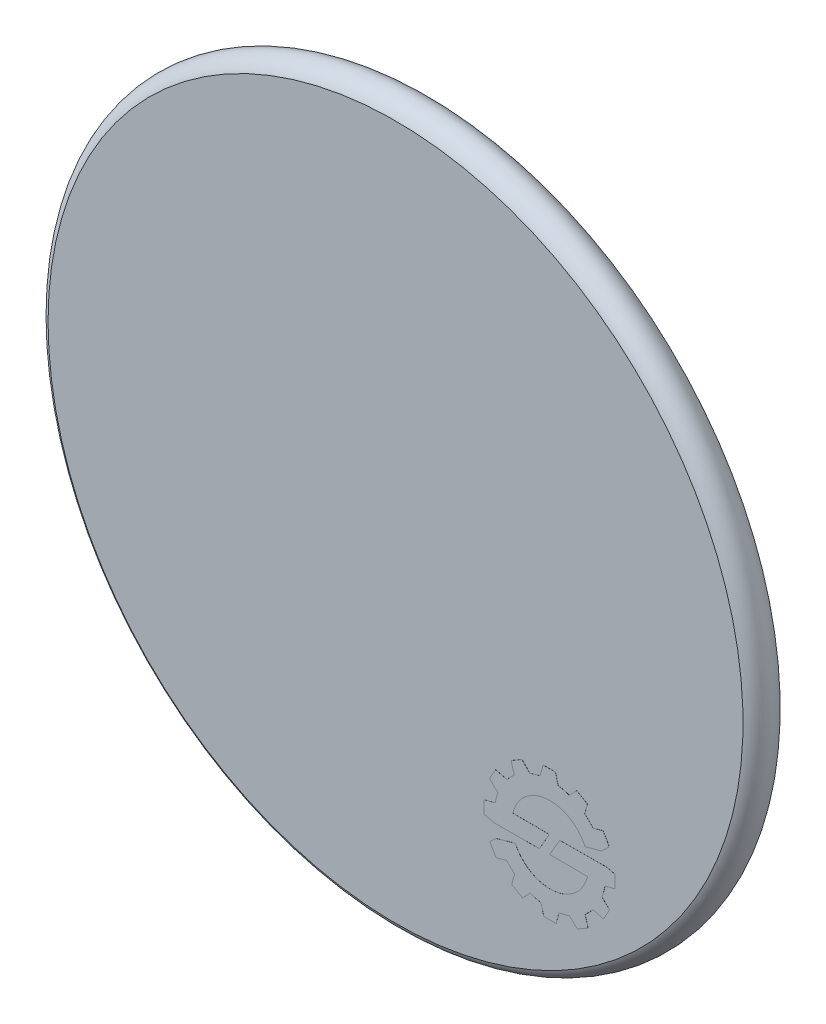
SolidWorks part; units mm, degrees
ref_plane "Front Plane" through (0, 0, 0) normal (0, 0, 1) x (1, 0, 0)
ref_plane "Top Plane" through (0, 0, 0) normal (0, 1, 0) x (1, 0, 0)
ref_plane "Right Plane" through (0, 0, 0) normal (1, 0, 0) x (0, 0, -1)
sketch "Sketch1" plane through (0, 0, 0) normal (0, 1, 0) x (1, 0, 0)
  line L0 (0, 0) -> (-40, 0)
  line L3 (-40, 0) -> (-42, 1.5)
  line L4 (0, 0) -> (0, -3)
  line L5 (0, -3) -> (-42, -3)
  line L6 (-42, -3) -> (-44.5, -3)
  line L8 (-44.5, 1.5) -> (-42, 1.5)
  arc A0 (-44.5, 1.5) -> (-44.5, -3) centre (-43.5625, -0.75) ccw
  dimension "D1" = 40
  dimension "D2" = 42
revolve "Revolve1" add sketch "Sketch1" angle 360 about L4
sketch "Sketch5" plane through (0, 0, 3) normal (0, 0, 1) x (1, 0, 0)
  line L0 (16.6947, -18.7297) -> (16.1934, -18.2222)
  line L1 (16.1934, -18.2222) -> (16.1083, -18.2709)
  line L2 (14.8898, -18.991) -> (14.8169, -19.0457)
  line L3 (14.8169, -19.0457) -> (14.8685, -19.2432)
  line L4 (15.1116, -20.0667) -> (15.221, -20.4222)
  line L5 (15.221, -20.4222) -> (14.8777, -20.7655)
  line L6 (12.1187, -22.2757) -> (12.0518, -22.4124)
  line L7 (12.0518, -22.4124) -> (12.3374, -22.6859)
  line L8 (12.1004, -26.8973) -> (12.617, -27.0189)
  line L9 (12.617, -27.0189) -> (15.4915, -27.0189)
  line L10 (24.1878, -23.6491) -> (24.2911, -23.8497)
  line L11 (24.2911, -23.8497) -> (24.4856, -23.798)
  line L12 (25.543, -23.5093) -> (26.3999, -23.2723)
  line L13 (26.3999, -23.2723) -> (26.886, -22.8014)
  line L14 (26.6186, -21.0056) -> (26.5609, -20.9326)
  line L15 (26.5609, -20.9326) -> (26.2145, -21.0329)
  line L16 (24.4734, -20.4404) -> (24.2364, -20.2277)
  line L17 (24.2364, -20.2277) -> (24.3914, -19.6808)
  line L18 (23.4221, -18.3013) -> (23.1942, -18.1706)
  line L19 (23.1942, -18.1706) -> (22.7202, -18.6659)
  line L20 (22.7202, -18.6659) -> (22.2462, -19.1612)
  line L21 (22.2462, -19.1612) -> (22.0669, -19.0943)
  line L22 (20.5294, -17.5963) -> (20.496, -17.4778)
  line L23 (20.496, -17.4778) -> (19.6938, -17.4778)
  line L24 (20.3805, -25.8885) -> (19.7515, -26.9885)
  line L25 (19.7515, -26.9885) -> (22.1641, -26.9885)
  line L26 (12.4438, -29.0486) -> (12.0822, -29.4102)
  line L27 (12.0822, -29.4102) -> (12.2189, -29.6351)
  line L28 (14.747, -30.8961) -> (15.2544, -31.4035)
  line L29 (15.2544, -31.4035) -> (15.1299, -31.8623)
  line L30 (16.1721, -33.4697) -> (16.2906, -33.5274)
  line L31 (16.2906, -33.5274) -> (16.4608, -33.3482)
  line L32 (16.9408, -32.8438) -> (17.2538, -32.5156)
  line L33 (17.2538, -32.5156) -> (17.5273, -32.6098)
  line L34 (20.3562, -34.2202) -> (20.5871, -34.2202)
  line L35 (20.5871, -34.2202) -> (20.7451, -33.567)
  line L36 (25.2057, -30.4403) -> (25.3029, -30.3218)
  line L37 (25.3029, -30.3218) -> (25.6007, -30.4069)
  line L38 (26.2692, -30.5892) -> (26.6399, -30.6894)
  line L39 (26.6399, -30.6894) -> (26.7888, -30.4281)
  line L40 (26.6916, -28.5928) -> (26.4485, -28.3649)
  line L41 (26.4485, -28.3649) -> (26.5731, -27.9882)
  line L42 (27.5089, -26.7606) -> (28.1166, -26.6087)
  line L43 (28.1166, -26.6087) -> (28.1166, -25.8034)
  line L44 (28.1166, -25.8034) -> (28.1166, -24.9982)
  line L45 (28.1166, -24.9982) -> (27.6153, -24.8706)
  line L46 (27.6153, -24.8706) -> (27.1139, -24.746)
  line L47 (27.1139, -24.746) -> (24.1209, -24.746)
  spline S0 degree 3 poles (18.8916, -17.4839) (18.8916, -17.49) (18.8126, -17.7999) (18.7184, -18.1767) knots 0 0 0 0 1 1 1 1
  spline S1 degree 3 poles (18.7184, -18.1767) (18.5239, -18.9424) (18.5756, -18.8603) (18.2262, -18.9393) knots 0 0 0 0 1 1 1 1
  spline S2 degree 3 poles (18.2262, -18.9393) (18.135, -18.9576) (17.8737, -19.0335) (17.6488, -19.1065) knots 0 0 0 0 1 1 1 1
  spline S3 degree 3 poles (17.6488, -19.1065) (17.424, -19.1794) (17.2295, -19.2402) (17.2174, -19.2402) knots 0 0 0 0 1 1 1 1
  spline S4 degree 3 poles (17.2174, -19.2402) (17.2052, -19.2402) (16.9682, -19.0123) (16.6947, -18.7297) knots 0 0 0 0 1 1 1 1
  spline S5 degree 3 poles (16.1083, -18.2709) (15.3881, -18.6871) (14.9476, -18.9485) (14.8898, -18.991) knots 0 0 0 0 1 1 1 1
  spline S6 degree 3 poles (14.8685, -19.2432) (14.9232, -19.4529) (14.9415, -19.5197) (15.1116, -20.0667) knots 0 0 0 0 1 1 1 1
  spline S7 degree 3 poles (14.8777, -20.7655) (14.6893, -20.9539) (14.4796, -21.1727) (14.4128, -21.2517) knots 0 0 0 0 1 1 1 1
  spline S8 degree 3 poles (14.4128, -21.2517) (14.3459, -21.3307) (14.27, -21.3975) (14.2456, -21.3975) knots 0 0 0 0 1 1 1 1
  spline S9 degree 3 poles (14.2456, -21.3975) (14.2213, -21.3975) (14.0573, -21.355) (13.881, -21.3064) knots 0 0 0 0 1 1 1 1
  spline S10 degree 3 poles (13.881, -21.3064) (13.2399, -21.121) (12.8418, -21.0268) (12.8175, -21.0511) knots 0 0 0 0 1 1 1 1
  spline S11 degree 3 poles (12.8175, -21.0511) (12.8054, -21.0663) (12.7324, -21.1879) (12.6595, -21.3216) knots 0 0 0 0 1 1 1 1
  spline S12 degree 3 poles (12.6595, -21.3216) (12.5836, -21.4553) (12.4468, -21.6953) (12.3557, -21.8533) knots 0 0 0 0 1 1 1 1
  spline S13 degree 3 poles (12.3557, -21.8533) (12.2645, -22.0113) (12.1582, -22.2028) (12.1187, -22.2757) knots 0 0 0 0 1 1 1 1
  spline S14 degree 3 poles (12.3374, -22.6859) (12.4924, -22.8378) (12.7324, -23.0687) (12.8722, -23.2024) knots 0 0 0 0 1 1 1 1
  spline S15 degree 3 poles (12.8722, -23.2024) (13.009, -23.3331) (13.1214, -23.4486) (13.1214, -23.4546) knots 0 0 0 0 1 1 1 1
  spline S16 degree 3 poles (13.1214, -23.4546) (13.1214, -23.4638) (13.0819, -23.5792) (13.0333, -23.716) knots 0 0 0 0 1 1 1 1
  spline S17 degree 3 poles (13.0333, -23.716) (12.9877, -23.8527) (12.9178, -24.1019) (12.8783, -24.269) knots 0 0 0 0 1 1 1 1
  spline S18 degree 3 poles (12.8783, -24.269) (12.8418, -24.4361) (12.8023, -24.6123) (12.7902, -24.6609) knots 0 0 0 0 1 1 1 1
  spline S19 degree 3 poles (12.7902, -24.6609) (12.7689, -24.7491) (12.7568, -24.7551) (12.3162, -24.8645) knots 0 0 0 0 1 1 1 1
  spline S20 degree 3 poles (12.3162, -24.8645) (12.064, -24.9253) (11.7571, -25.0013) (11.6325, -25.0316) knots 0 0 0 0 1 1 1 1
  spline S21 degree 3 poles (11.6325, -25.0316) (11.5079, -25.059) (11.3864, -25.0955) (11.3651, -25.1137) knots 0 0 0 0 1 1 1 1
  spline S22 degree 3 poles (11.3651, -25.1137) (11.3377, -25.135) (11.3286, -25.3234) (11.3317, -25.8916) knots 0 0 0 0 1 1 1 1
  spline S23 degree 3 poles (11.3317, -25.8916) (11.3317, -26.3018) (11.3469, -26.6603) (11.359, -26.6877) knots 0 0 0 0 1 1 1 1
  spline S24 degree 3 poles (11.359, -26.6877) (11.3742, -26.715) (11.4319, -26.7454) (11.4866, -26.7545) knots 0 0 0 0 1 1 1 1
  spline S25 degree 3 poles (11.4866, -26.7545) (11.5413, -26.7636) (11.8178, -26.8274) (12.1004, -26.8973) knots 0 0 0 0 1 1 1 1
  spline S26 degree 3 poles (15.4915, -27.0189) (17.7461, -27.0189) (18.3781, -27.0097) (18.4145, -26.9794) knots 0 0 0 0 1 1 1 1
  spline S27 degree 3 poles (18.4145, -26.9794) (18.4389, -26.9611) (18.5969, -26.7029) (18.764, -26.4112) knots 0 0 0 0 1 1 1 1
  spline S28 degree 3 poles (18.764, -26.4112) (18.9311, -26.1195) (19.2076, -25.6394) (19.3778, -25.3446) knots 0 0 0 0 1 1 1 1
  spline S29 degree 3 poles (19.3778, -25.3446) (19.5449, -25.0499) (19.6847, -24.7977) (19.6847, -24.7886) knots 0 0 0 0 1 1 1 1
  spline S30 degree 3 poles (19.6847, -24.7886) (19.6847, -24.7794) (18.6394, -24.7703) (17.3602, -24.7703) knots 0 0 0 0 1 1 1 1
  spline S31 degree 3 poles (17.3602, -24.7703) (15.139, -24.7703) (15.0357, -24.7673) (15.0357, -24.7156) knots 0 0 0 0 1 1 1 1
  spline S32 degree 3 poles (15.0357, -24.7156) (15.0357, -24.6458) (15.218, -24.1079) (15.3152, -23.8892) knots 0 0 0 0 1 1 1 1
  spline S33 degree 3 poles (15.3152, -23.8892) (16.1295, -22.0691) (18.0074, -20.8992) (19.9733, -20.9843) knots 0 0 0 0 1 1 1 1
  spline S34 degree 3 poles (19.9733, -20.9843) (21.4926, -21.0481) (22.7809, -21.7105) (23.7077, -22.8955) knots 0 0 0 0 1 1 1 1
  spline S35 degree 3 poles (23.7077, -22.8955) (23.8171, -23.0384) (23.9082, -23.1599) (23.9082, -23.169) knots 0 0 0 0 1 1 1 1
  spline S36 degree 3 poles (23.9082, -23.169) (23.9082, -23.1781) (23.9478, -23.245) (23.9964, -23.3179) knots 0 0 0 0 1 1 1 1
  spline S37 degree 3 poles (23.9964, -23.3179) (24.0419, -23.3908) (24.1301, -23.5397) (24.1878, -23.6491) knots 0 0 0 0 1 1 1 1
  spline S38 degree 3 poles (24.4856, -23.798) (24.595, -23.7706) (25.069, -23.64) (25.543, -23.5093) knots 0 0 0 0 1 1 1 1
  spline S39 degree 3 poles (26.886, -22.8014) (27.1534, -22.54) (27.3722, -22.3182) (27.3722, -22.3061) knots 0 0 0 0 1 1 1 1
  spline S40 degree 3 poles (27.3722, -22.3061) (27.3722, -22.2909) (27.2324, -22.0447) (27.0653, -21.7561) knots 0 0 0 0 1 1 1 1
  spline S41 degree 3 poles (27.0653, -21.7561) (26.8951, -21.4674) (26.7371, -21.197) (26.7159, -21.1545) knots 0 0 0 0 1 1 1 1
  spline S42 degree 3 poles (26.7159, -21.1545) (26.6916, -21.1119) (26.649, -21.0451) (26.6186, -21.0056) knots 0 0 0 0 1 1 1 1
  spline S43 degree 3 poles (26.2145, -21.0329) (26.0231, -21.0846) (25.7648, -21.1636) (25.6372, -21.2031) knots 0 0 0 0 1 1 1 1
  spline S44 degree 3 poles (25.6372, -21.2031) (25.5096, -21.2426) (25.385, -21.276) (25.3576, -21.276) knots 0 0 0 0 1 1 1 1
  spline S45 degree 3 poles (25.3576, -21.276) (25.3333, -21.276) (25.2513, -21.2122) (25.1784, -21.1332) knots 0 0 0 0 1 1 1 1
  spline S46 degree 3 poles (25.1784, -21.1332) (24.9596, -20.8962) (24.7256, -20.6652) (24.4734, -20.4404) knots 0 0 0 0 1 1 1 1
  spline S47 degree 3 poles (24.3914, -19.6808) (24.6071, -18.912) (24.6041, -18.9637) (24.4643, -18.8907) knots 0 0 0 0 1 1 1 1
  spline S48 degree 3 poles (24.4643, -18.8907) (24.4005, -18.8573) (24.1908, -18.7388) (23.9994, -18.6294) knots 0 0 0 0 1 1 1 1
  spline S49 degree 3 poles (23.9994, -18.6294) (23.808, -18.52) (23.5467, -18.3711) (23.4221, -18.3013) knots 0 0 0 0 1 1 1 1
  spline S50 degree 3 poles (22.0669, -19.0943) (21.8299, -19.0092) (21.3467, -18.8847) (21.1584, -18.8603) knots 0 0 0 0 1 1 1 1
  spline S51 degree 3 poles (21.1584, -18.8603) (20.815, -18.8148) (20.8363, -18.8421) (20.6935, -18.3043) knots 0 0 0 0 1 1 1 1
  spline S52 degree 3 poles (20.6935, -18.3043) (20.6236, -18.0399) (20.5658, -17.7999) (20.5658, -17.7695) knots 0 0 0 0 1 1 1 1
  spline S53 degree 3 poles (20.5658, -17.7695) (20.5658, -17.7391) (20.5506, -17.6601) (20.5294, -17.5963) knots 0 0 0 0 1 1 1 1
  spline S54 degree 3 poles (19.6938, -17.4778) (19.2562, -17.4778) (18.8946, -17.4808) (18.8916, -17.4839) knots 0 0 0 0 1 1 1 1
  spline S55 degree 3 poles (21.0702, -24.7673) (21.0368, -24.7794) (20.7542, -25.2413) (20.3805, -25.8885) knots 0 0 0 0 1 1 1 1
  spline S56 degree 3 poles (22.1641, -26.9885) (24.1453, -26.9885) (24.5767, -26.9946) (24.5767, -27.028) knots 0 0 0 0 1 1 1 1
  spline S57 degree 3 poles (24.5767, -27.028) (24.5767, -27.0523) (24.5433, -27.1829) (24.5008, -27.3197) knots 0 0 0 0 1 1 1 1
  spline S58 degree 3 poles (24.5008, -27.3197) (24.285, -28.0398) (23.8171, -28.8116) (23.2762, -29.3494) knots 0 0 0 0 1 1 1 1
  spline S59 degree 3 poles (23.2762, -29.3494) (22.5774, -30.0361) (21.8238, -30.4433) (20.8089, -30.6834) knots 0 0 0 0 1 1 1 1
  spline S60 degree 3 poles (20.8089, -30.6834) (20.3228, -30.7958) (19.5631, -30.814) (19.0466, -30.7259) knots 0 0 0 0 1 1 1 1
  spline S61 degree 3 poles (19.0466, -30.7259) (17.6124, -30.4767) (16.5306, -29.787) (15.7011, -28.5837) knots 0 0 0 0 1 1 1 1
  spline S62 degree 3 poles (15.7011, -28.5837) (15.6434, -28.4986) (15.5401, -28.3254) (15.4763, -28.1978) knots 0 0 0 0 1 1 1 1
  spline S63 degree 3 poles (15.4763, -28.1978) (15.4094, -28.0672) (15.3395, -27.9608) (15.3243, -27.9608) knots 0 0 0 0 1 1 1 1
  spline S64 degree 3 poles (15.3243, -27.9608) (15.3061, -27.9608) (15.1754, -27.9942) (15.0357, -28.0337) knots 0 0 0 0 1 1 1 1
  spline S65 degree 3 poles (15.0357, -28.0337) (14.8929, -28.0763) (14.3672, -28.2191) (13.8658, -28.3558) knots 0 0 0 0 1 1 1 1
  spline S66 degree 3 poles (13.8658, -28.3558) (13.3645, -28.4956) (12.9208, -28.6232) (12.8783, -28.6445) knots 0 0 0 0 1 1 1 1
  spline S67 degree 3 poles (12.8783, -28.6445) (12.8358, -28.6688) (12.6413, -28.8481) (12.4438, -29.0486) knots 0 0 0 0 1 1 1 1
  spline S68 degree 3 poles (12.2189, -29.6351) (12.3496, -29.8538) (12.5289, -30.1577) (12.6352, -30.3461) knots 0 0 0 0 1 1 1 1
  spline S69 degree 3 poles (12.6352, -30.3461) (12.6626, -30.3947) (12.7324, -30.5102) (12.7871, -30.6013) knots 0 0 0 0 1 1 1 1
  spline S70 degree 3 poles (12.7871, -30.6013) (12.8844, -30.7593) (12.8904, -30.7624) (13.0029, -30.7441) knots 0 0 0 0 1 1 1 1
  spline S71 degree 3 poles (13.0029, -30.7441) (13.0667, -30.735) (13.2247, -30.6925) (13.3553, -30.653) knots 0 0 0 0 1 1 1 1
  spline S72 degree 3 poles (13.3553, -30.653) (13.486, -30.6104) (13.7261, -30.5375) (13.8901, -30.4859) knots 0 0 0 0 1 1 1 1
  spline S73 degree 3 poles (13.8901, -30.4859) (14.0542, -30.4342) (14.2001, -30.3917) (14.2153, -30.3917) knots 0 0 0 0 1 1 1 1
  spline S74 degree 3 poles (14.2153, -30.3917) (14.2305, -30.3917) (14.4705, -30.6196) (14.747, -30.8961) knots 0 0 0 0 1 1 1 1
  spline S75 degree 3 poles (15.1299, -31.8623) (15.06, -32.1145) (14.9749, -32.4062) (14.9445, -32.5126) knots 0 0 0 0 1 1 1 1
  spline S76 degree 3 poles (14.9445, -32.5126) (14.8898, -32.6949) (14.8898, -32.7921) (14.9476, -32.7921) knots 0 0 0 0 1 1 1 1
  spline S77 degree 3 poles (14.9476, -32.7921) (14.9627, -32.7921) (15.0387, -32.8316) (15.1177, -32.8772) knots 0 0 0 0 1 1 1 1
  spline S78 degree 3 poles (15.1177, -32.8772) (15.3729, -33.0322) (16.0505, -33.4089) (16.1721, -33.4697) knots 0 0 0 0 1 1 1 1
  spline S79 degree 3 poles (16.4608, -33.3482) (16.5549, -33.2509) (16.7707, -33.023) (16.9408, -32.8438) knots 0 0 0 0 1 1 1 1
  spline S80 degree 3 poles (17.5273, -32.6098) (17.7795, -32.6949) (18.2687, -32.8195) (18.5361, -32.865) knots 0 0 0 0 1 1 1 1
  spline S81 degree 3 poles (18.5361, -32.865) (18.6303, -32.8833) (18.6485, -32.8985) (18.6667, -32.9835) knots 0 0 0 0 1 1 1 1
  spline S82 degree 3 poles (18.6667, -32.9835) (18.7123, -33.2145) (18.9676, -34.1777) (18.9919, -34.2081) knots 0 0 0 0 1 1 1 1
  spline S83 degree 3 poles (18.9919, -34.2081) (19.0101, -34.2324) (19.1833, -34.2415) (19.5722, -34.2324) knots 0 0 0 0 1 1 1 1
  spline S84 degree 3 poles (19.5722, -34.2324) (19.8761, -34.2263) (20.2286, -34.2233) (20.3562, -34.2202) knots 0 0 0 0 1 1 1 1
  spline S85 degree 3 poles (20.7451, -33.567) (20.8332, -33.2084) (20.9244, -32.9015) (20.9457, -32.8833) knots 0 0 0 0 1 1 1 1
  spline S86 degree 3 poles (20.9457, -32.8833) (20.9639, -32.8681) (21.055, -32.8377) (21.1462, -32.8225) knots 0 0 0 0 1 1 1 1
  spline S87 degree 3 poles (21.1462, -32.8225) (21.3802, -32.78) (22.0942, -32.5764) (22.1307, -32.546) knots 0 0 0 0 1 1 1 1
  spline S88 degree 3 poles (22.1307, -32.546) (22.1459, -32.5308) (22.1945, -32.5186) (22.2431, -32.5186) knots 0 0 0 0 1 1 1 1
  spline S89 degree 3 poles (22.2431, -32.5186) (22.31, -32.5186) (22.4133, -32.6068) (22.787, -32.9896) knots 0 0 0 0 1 1 1 1
  spline S90 degree 3 poles (22.787, -32.9896) (23.0423, -33.2479) (23.2732, -33.4606) (23.2975, -33.4606) knots 0 0 0 0 1 1 1 1
  spline S91 degree 3 poles (23.2975, -33.4606) (23.3248, -33.4606) (23.3735, -33.4424) (23.4069, -33.4181) knots 0 0 0 0 1 1 1 1
  spline S92 degree 3 poles (23.4069, -33.4181) (23.4403, -33.3968) (23.5163, -33.3512) (23.574, -33.3178) knots 0 0 0 0 1 1 1 1
  spline S93 degree 3 poles (23.574, -33.3178) (23.6895, -33.2509) (23.9721, -33.0869) (24.1361, -32.9896) knots 0 0 0 0 1 1 1 1
  spline S94 degree 3 poles (24.1361, -32.9896) (24.1939, -32.9562) (24.3306, -32.8772) (24.44, -32.8134) knots 0 0 0 0 1 1 1 1
  spline S95 degree 3 poles (24.44, -32.8134) (24.6648, -32.6827) (24.6679, -32.6706) (24.5767, -32.3698) knots 0 0 0 0 1 1 1 1
  spline S96 degree 3 poles (24.5767, -32.3698) (24.3944, -31.762) (24.3033, -31.44) (24.3033, -31.3913) knots 0 0 0 0 1 1 1 1
  spline S97 degree 3 poles (24.3033, -31.3913) (24.3033, -31.364) (24.3549, -31.2941) (24.4187, -31.2364) knots 0 0 0 0 1 1 1 1
  spline S98 degree 3 poles (24.4187, -31.2364) (24.598, -31.0753) (25.0994, -30.5709) (25.2057, -30.4403) knots 0 0 0 0 1 1 1 1
  spline S99 degree 3 poles (25.6007, -30.4069) (25.7648, -30.4524) (26.0656, -30.5345) (26.2692, -30.5892) knots 0 0 0 0 1 1 1 1
  spline S100 degree 3 poles (26.7888, -30.4281) (27.2871, -29.5439) (27.4026, -29.3312) (27.4026, -29.3039) knots 0 0 0 0 1 1 1 1
  spline S101 degree 3 poles (27.4026, -29.3039) (27.4026, -29.2765) (27.2659, -29.1367) (26.6916, -28.5928) knots 0 0 0 0 1 1 1 1
  spline S102 degree 3 poles (26.5731, -27.9882) (26.6429, -27.7815) (26.7311, -27.4595) (26.7675, -27.2771) knots 0 0 0 0 1 1 1 1
  spline S103 degree 3 poles (26.7675, -27.2771) (26.807, -27.0918) (26.8526, -26.9368) (26.8708, -26.9277) knots 0 0 0 0 1 1 1 1
  spline S104 degree 3 poles (26.8708, -26.9277) (26.886, -26.9216) (27.1747, -26.8457) (27.5089, -26.7606) knots 0 0 0 0 1 1 1 1
  spline S105 degree 3 poles (24.1209, -24.746) (22.4741, -24.746) (21.1006, -24.7551) (21.0702, -24.7673) knots 0 0 0 0 1 1 1 1
extrude "Boss-Extrude2" add sketch "Sketch5" along normal blind 0.01
sketch "Sketch8" plane through (0, 0, 0) normal (0, 0, -1) x (-1, 0, 0)
  line L0 (-1.1168, 18.2598) -> (-0.383, 18.161)
  line L1 (-0.383, 18.161) -> (-0.383, 17.3426)
  line L2 (-7.0999, 8.0574) -> (-7.495, 6.8721)
  line L3 (-7.495, 6.8721) -> (-8.638, 6.9709)
  line L4 (-23.2572, -11.43) -> (-21.4086, -9.4968)
  line L5 (-10.9946, -5.6303) -> (-10.7124, -6.477)
  line L6 (-10.7124, -6.477) -> (-11.0087, -6.6746)
  line L7 (-16.3427, -7.4789) -> (-20.1386, -7.4648)
  line L8 (-20.1386, -7.4648) -> (-20.4914, -7.8176)
  line L9 (-20.4914, -12.2061) -> (-20.1527, -12.5589)
  line L10 (-20.1527, -12.5589) -> (0.1532, -12.5589)
  line L11 (0.1532, -12.5589) -> (20.4591, -12.5589)
  line L12 (20.4591, -12.5589) -> (20.8401, -12.2626)
  line L13 (11.3715, -6.6746) -> (11.0752, -6.477)
  line L14 (11.0752, -6.477) -> (11.3574, -5.6303)
  line L15 (21.7714, -9.5109) -> (23.62, -11.43)
  line L16 (8.9868, 6.9709) -> (7.8296, 6.8721)
  line L17 (7.8296, 6.8721) -> (7.6039, 7.6764)
  line L18 (1.4373, 16.3266) -> (0.7459, 16.5806)
  line L19 (0.7459, 16.5806) -> (0.7459, 17.3849)
  line L20 (0.7459, 17.3849) -> (0.7459, 18.1751)
  line L21 (0.7459, 18.1751) -> (1.6349, 18.2598)
  line L22 (3.4975, 18.7678) -> (3.4975, 19.1206)
  line L23 (3.4975, 19.1206) -> (0.1391, 19.1629)
  line L24 (-3.9531, 6.5899) -> (-4.9268, 6.6746)
  line L25 (-4.9268, 6.6746) -> (-4.828, 7.3237)
  line L26 (-6.2815, -1.5381) -> (-5.7735, -3.0762)
  line L27 (-5.7735, -3.0762) -> (-6.4367, -3.1609)
  line L28 (-9.7105, -3.4713) -> (-10.3737, -3.556)
  line L29 (-10.3737, -3.556) -> (-10.7406, -2.4553)
  line L30 (11.1175, -2.3989) -> (10.7365, -3.5419)
  line L31 (10.7365, -3.5419) -> (9.9463, -3.4572)
  line L32 (-14.9598, -3.9088) -> (-15.6371, -3.9934)
  line L33 (-15.6371, -3.9934) -> (-15.5948, -3.2456)
  line L34 (-15.5948, -3.2456) -> (-15.5525, -2.4977)
  line L35 (-15.5525, -2.4977) -> (-14.0003, -2.032)
  line L36 (15.9577, -3.2456) -> (16, -3.9934)
  line L37 (16, -3.9934) -> (15.3227, -3.9088)
  line L38 (14.3208, -2.0461) -> (15.9153, -2.4977)
  line L39 (15.9153, -2.4977) -> (15.9577, -3.2456)
  line L40 (-4.8986, -5.9267) -> (-4.4329, -7.493)
  line L41 (-4.4329, -7.493) -> (-4.7293, -7.874)
  line L42 (-5.8158, -9.7649) -> (-5.9146, -10.16)
  line L43 (-5.9146, -10.16) -> (-4.7716, -10.16)
  line L44 (5.1344, -10.16) -> (6.2774, -10.16)
  line L45 (6.2774, -10.16) -> (6.1786, -9.7649)
  line L46 (5.0921, -7.874) -> (4.7958, -7.493)
  line L47 (4.7958, -7.493) -> (5.2614, -5.9267)
  line L48 (11.1175, -9.652) -> (10.2709, -10.7103)
  line L49 (10.2709, -10.7103) -> (0.1814, -10.7103)
  line L50 (0.1814, -10.7103) -> (-9.908, -10.7103)
  line L51 (-9.908, -10.7103) -> (-10.7124, -9.6943)
  line L52 (-5.9428, -4.3886) -> (-5.3643, -4.3744)
  line L53 (-5.3643, -4.3744) -> (-4.8986, -5.9267)
  line L54 (-14.0003, -9.9483) -> (-14.0003, -10.795)
  line L55 (-14.0003, -10.795) -> (-16.6814, -10.795)
  line L56 (-16.6814, -10.795) -> (-19.3625, -10.795)
  line L57 (-19.3625, -10.795) -> (-19.4048, -10.1036)
  line L58 (-16.6531, -9.0593) -> (-14.0003, -9.1017)
  line L59 (-14.0003, -9.1017) -> (-14.0003, -9.9483)
  line L60 (19.7253, -9.9483) -> (19.7253, -10.795)
  line L61 (19.7253, -10.795) -> (17.0442, -10.795)
  line L62 (17.0442, -10.795) -> (14.3631, -10.795)
  line L63 (14.3631, -10.795) -> (14.3208, -10.1036)
  line L64 (17.0724, -9.0593) -> (19.7253, -9.1017)
  line L65 (19.7253, -9.1017) -> (19.7253, -9.9483)
  line L66 (-12.5327, 8.89) -> (-7.4668, 8.89)
  line L67 (-7.4668, 8.89) -> (-7.0858, 9.8496)
  line L68 (-6.0134, 12.1073) -> (-5.3219, 13.4056)
  line L69 (-5.3219, 13.4056) -> (-10.6841, 13.4056)
  line L70 (-10.6841, 13.4056) -> (-16.0464, 13.4056)
  line L71 (-16.0464, 13.4056) -> (-16.0464, 12.5166)
  line L72 (7.5333, 9.7085) -> (7.8579, 8.89)
  line L73 (7.8579, 8.89) -> (12.9096, 8.89)
  line L74 (16.4092, 12.5307) -> (16.4092, 13.4056)
  line L75 (16.4092, 13.4056) -> (11.047, 13.4056)
  line L76 (11.047, 13.4056) -> (5.6989, 13.4056)
  line L77 (5.6989, 13.4056) -> (6.4468, 11.9662)
  spline S0 degree 3 poles (-3.2899, 18.9795) (-3.4592, 18.542) (-3.2335, 18.3445) (-2.542, 18.3445) knots 0 0 0 0 1 1 1 1
  spline S1 degree 3 poles (-2.542, 18.3445) (-2.1751, 18.3445) (-1.526, 18.3021) (-1.1168, 18.2598) knots 0 0 0 0 1 1 1 1
  spline S2 degree 3 poles (-0.383, 17.3426) (-0.383, 16.7358) (-0.4395, 16.51) (-0.5665, 16.51) knots 0 0 0 0 1 1 1 1
  spline S3 degree 3 poles (-0.5665, 16.51) (-0.6794, 16.51) (-1.145, 16.3125) (-1.6248, 16.0867) knots 0 0 0 0 1 1 1 1
  spline S4 degree 3 poles (-1.6248, 16.0867) (-2.6267, 15.5787) (-3.7838, 14.478) (-4.6164, 13.2503) knots 0 0 0 0 1 1 1 1
  spline S5 degree 3 poles (-4.6164, 13.2503) (-5.3643, 12.1497) (-6.5919, 9.5956) (-7.0999, 8.0574) knots 0 0 0 0 1 1 1 1
  spline S6 degree 3 poles (-8.638, 6.9709) (-12.2505, 7.2531) (-12.702, 7.2531) (-13.1395, 6.9144) knots 0 0 0 0 1 1 1 1
  spline S7 degree 3 poles (-13.1395, 6.9144) (-13.7745, 6.3923) (-14.353, 5.5033) (-14.353, 5.0236) knots 0 0 0 0 1 1 1 1
  spline S8 degree 3 poles (-14.353, 5.0236) (-14.353, 4.7837) (-13.9861, 3.4996) (-13.5487, 2.159) knots 0 0 0 0 1 1 1 1
  spline S9 degree 3 poles (-13.5487, 2.159) (-13.0971, 0.8184) (-12.7726, -0.3104) (-12.8149, -0.3528) knots 0 0 0 0 1 1 1 1
  spline S10 degree 3 poles (-12.8149, -0.3528) (-12.9137, -0.4516) (-15.1997, -1.1148) (-15.4396, -1.1289) knots 0 0 0 0 1 1 1 1
  spline S11 degree 3 poles (-15.4396, -1.1289) (-15.5807, -1.1289) (-15.623, -0.6632) (-15.623, 0.762) knots 0 0 0 0 1 1 1 1
  spline S12 degree 3 poles (-15.623, 0.762) (-15.623, 2.3001) (-15.6654, 2.7093) (-15.8488, 2.8787) knots 0 0 0 0 1 1 1 1
  spline S13 degree 3 poles (-15.8488, 2.8787) (-16.0323, 3.0762) (-16.639, 3.1044) (-20.3644, 3.1044) knots 0 0 0 0 1 1 1 1
  spline S14 degree 3 poles (-20.3644, 3.1044) (-23.0596, 3.1044) (-24.7812, 3.048) (-24.9505, 2.9633) knots 0 0 0 0 1 1 1 1
  spline S15 degree 3 poles (-24.9505, 2.9633) (-25.2045, 2.8222) (-25.2186, 2.5823) (-25.2186, -4.1628) knots 0 0 0 0 1 1 1 1
  spline S16 degree 3 poles (-25.2186, -4.1628) (-25.2186, -10.9079) (-25.2045, -11.1478) (-24.9505, -11.2889) knots 0 0 0 0 1 1 1 1
  spline S17 degree 3 poles (-24.9505, -11.2889) (-24.7953, -11.3595) (-24.0333, -11.43) (-23.2572, -11.43) knots 0 0 0 0 1 1 1 1
  spline S18 degree 3 poles (-21.4086, -9.4968) (-21.4086, -7.8881) (-21.2393, -7.3519) (-20.6043, -7.0697) knots 0 0 0 0 1 1 1 1
  spline S19 degree 3 poles (-20.6043, -7.0697) (-20.4067, -6.985) (-19.3625, -6.9144) (-18.1207, -6.9144) knots 0 0 0 0 1 1 1 1
  spline S20 degree 3 poles (-18.1207, -6.9144) (-16.6249, -6.9144) (-15.9053, -6.858) (-15.7924, -6.7451) knots 0 0 0 0 1 1 1 1
  spline S21 degree 3 poles (-15.7924, -6.7451) (-15.6936, -6.6463) (-15.623, -6.2794) (-15.623, -5.9126) knots 0 0 0 0 1 1 1 1
  spline S22 degree 3 poles (-15.623, -5.9126) (-15.623, -5.1223) (-15.6654, -5.1364) (-13.4358, -5.0094) knots 0 0 0 0 1 1 1 1
  spline S23 degree 3 poles (-13.4358, -5.0094) (-12.6597, -4.9671) (-11.8554, -4.8966) (-11.6578, -4.8542) knots 0 0 0 0 1 1 1 1
  spline S24 degree 3 poles (-11.6578, -4.8542) (-11.305, -4.7837) (-11.2627, -4.8401) (-10.9946, -5.6303) knots 0 0 0 0 1 1 1 1
  spline S25 degree 3 poles (-11.0087, -6.6746) (-12.2787, -7.5071) (-12.2505, -7.493) (-16.3427, -7.4789) knots 0 0 0 0 1 1 1 1
  spline S26 degree 3 poles (-20.4914, -7.8176) (-20.83, -8.1562) (-20.8441, -8.2409) (-20.8441, -10.0189) knots 0 0 0 0 1 1 1 1
  spline S27 degree 3 poles (-20.8441, -10.0189) (-20.8441, -11.7969) (-20.83, -11.8816) (-20.4914, -12.2061) knots 0 0 0 0 1 1 1 1
  spline S28 degree 3 poles (20.8401, -12.2626) (21.207, -11.9803) (21.207, -11.9662) (21.207, -10.0189) knots 0 0 0 0 1 1 1 1
  spline S29 degree 3 poles (21.207, -10.0189) (21.207, -7.2813) (21.5457, -7.4648) (16.6773, -7.4789) knots 0 0 0 0 1 1 1 1
  spline S30 degree 3 poles (16.6773, -7.4789) (12.6133, -7.493) (12.6415, -7.493) (11.3715, -6.6746) knots 0 0 0 0 1 1 1 1
  spline S31 degree 3 poles (11.3574, -5.6303) (11.6255, -4.8401) (11.6679, -4.7837) (12.0206, -4.8542) knots 0 0 0 0 1 1 1 1
  spline S32 degree 3 poles (12.0206, -4.8542) (12.2182, -4.8966) (13.0225, -4.9671) (13.7986, -5.0094) knots 0 0 0 0 1 1 1 1
  spline S33 degree 3 poles (13.7986, -5.0094) (16.0282, -5.1364) (15.9859, -5.1223) (15.9859, -5.9126) knots 0 0 0 0 1 1 1 1
  spline S34 degree 3 poles (15.9859, -5.9126) (15.9859, -6.2794) (16.0564, -6.6463) (16.1552, -6.7451) knots 0 0 0 0 1 1 1 1
  spline S35 degree 3 poles (16.1552, -6.7451) (16.2681, -6.858) (16.9878, -6.9144) (18.4835, -6.9144) knots 0 0 0 0 1 1 1 1
  spline S36 degree 3 poles (18.4835, -6.9144) (19.8382, -6.9144) (20.7695, -6.9709) (20.9953, -7.0838) knots 0 0 0 0 1 1 1 1
  spline S37 degree 3 poles (20.9953, -7.0838) (21.6162, -7.366) (21.7714, -7.874) (21.7714, -9.5109) knots 0 0 0 0 1 1 1 1
  spline S38 degree 3 poles (23.62, -11.43) (24.3961, -11.43) (25.1581, -11.3595) (25.3133, -11.2889) knots 0 0 0 0 1 1 1 1
  spline S39 degree 3 poles (25.3133, -11.2889) (25.5673, -11.1478) (25.5814, -10.9079) (25.5814, -4.1628) knots 0 0 0 0 1 1 1 1
  spline S40 degree 3 poles (25.5814, -4.1628) (25.5814, 2.5823) (25.5673, 2.8222) (25.3133, 2.9633) knots 0 0 0 0 1 1 1 1
  spline S41 degree 3 poles (25.3133, 2.9633) (25.144, 3.048) (23.4224, 3.1044) (20.7272, 3.1044) knots 0 0 0 0 1 1 1 1
  spline S42 degree 3 poles (20.7272, 3.1044) (17.0019, 3.1044) (16.3951, 3.0762) (16.2117, 2.8787) knots 0 0 0 0 1 1 1 1
  spline S43 degree 3 poles (16.2117, 2.8787) (16.0282, 2.7093) (15.9859, 2.3001) (15.9859, 0.762) knots 0 0 0 0 1 1 1 1
  spline S44 degree 3 poles (15.9859, 0.762) (15.9859, -0.6632) (15.9435, -1.1289) (15.8165, -1.1289) knots 0 0 0 0 1 1 1 1
  spline S45 degree 3 poles (15.8165, -1.1289) (15.5625, -1.1148) (13.2765, -0.4516) (13.1778, -0.3528) knots 0 0 0 0 1 1 1 1
  spline S46 degree 3 poles (13.1778, -0.3528) (13.1354, -0.3104) (13.46, 0.8184) (13.9115, 2.159) knots 0 0 0 0 1 1 1 1
  spline S47 degree 3 poles (13.9115, 2.159) (14.349, 3.4996) (14.7159, 4.7837) (14.7159, 5.0236) knots 0 0 0 0 1 1 1 1
  spline S48 degree 3 poles (14.7159, 5.0236) (14.7159, 5.5033) (14.1373, 6.3923) (13.5023, 6.9144) knots 0 0 0 0 1 1 1 1
  spline S49 degree 3 poles (13.5023, 6.9144) (13.0649, 7.2531) (12.6133, 7.2531) (8.9868, 6.9709) knots 0 0 0 0 1 1 1 1
  spline S50 degree 3 poles (7.6039, 7.6764) (7.2652, 8.8195) (6.1786, 11.3453) (5.5719, 12.3472) knots 0 0 0 0 1 1 1 1
  spline S51 degree 3 poles (5.5719, 12.3472) (4.3865, 14.351) (2.8484, 15.8327) (1.4373, 16.3266) knots 0 0 0 0 1 1 1 1
  spline S52 degree 3 poles (1.6349, 18.2598) (2.1146, 18.3021) (2.7355, 18.3586) (3.0036, 18.3868) knots 0 0 0 0 1 1 1 1
  spline S53 degree 3 poles (3.0036, 18.3868) (3.427, 18.415) (3.4975, 18.4715) (3.4975, 18.7678) knots 0 0 0 0 1 1 1 1
  spline S54 degree 3 poles (0.1391, 19.1629) (-2.7537, 19.1911) (-3.2194, 19.1629) (-3.2899, 18.9795) knots 0 0 0 0 1 1 1 1
  spline S55 degree 3 poles (1.6066, 14.9437) (2.284, 14.605) (2.8343, 13.9418) (2.9472, 13.3209) knots 0 0 0 0 1 1 1 1
  spline S56 degree 3 poles (2.9472, 13.3209) (3.0742, 12.6012) (2.8908, 12.4742) (2.0582, 12.7141) knots 0 0 0 0 1 1 1 1
  spline S57 degree 3 poles (2.0582, 12.7141) (1.6913, 12.827) (0.8446, 12.9117) (0.1814, 12.9117) knots 0 0 0 0 1 1 1 1
  spline S58 degree 3 poles (0.1814, 12.9117) (-0.4818, 12.9117) (-1.3285, 12.827) (-1.6954, 12.7141) knots 0 0 0 0 1 1 1 1
  spline S59 degree 3 poles (-1.6954, 12.7141) (-2.5279, 12.4742) (-2.7114, 12.6012) (-2.5844, 13.3209) knots 0 0 0 0 1 1 1 1
  spline S60 degree 3 poles (-2.5844, 13.3209) (-2.2739, 14.9296) (-0.0726, 15.7903) (1.6066, 14.9437) knots 0 0 0 0 1 1 1 1
  spline S61 degree 3 poles (2.2275, 11.303) (3.2153, 10.8091) (4.0196, 10.0048) (4.5276, 8.9888) knots 0 0 0 0 1 1 1 1
  spline S62 degree 3 poles (4.5276, 8.9888) (4.8945, 8.255) (5.2332, 6.8298) (5.0639, 6.6746) knots 0 0 0 0 1 1 1 1
  spline S63 degree 3 poles (5.0639, 6.6746) (4.951, 6.5476) (-2.5561, 6.477) (-3.9531, 6.5899) knots 0 0 0 0 1 1 1 1
  spline S64 degree 3 poles (-4.828, 7.3237) (-4.6305, 8.6783) (-3.7133, 10.1882) (-2.6408, 10.9361) knots 0 0 0 0 1 1 1 1
  spline S65 degree 3 poles (-2.6408, 10.9361) (-1.145, 11.9803) (0.5906, 12.1073) (2.2275, 11.303) knots 0 0 0 0 1 1 1 1
  spline S66 degree 3 poles (-9.2307, 5.7714) (-6.8741, 5.6021) (-6.3661, 5.4892) (-7.0011, 5.2917) knots 0 0 0 0 1 1 1 1
  spline S67 degree 3 poles (-7.0011, 5.2917) (-7.5374, 5.1223) (-8.003, 4.6426) (-8.003, 4.2616) knots 0 0 0 0 1 1 1 1
  spline S68 degree 3 poles (-8.003, 4.2616) (-8.003, 4.0499) (-7.8196, 3.2879) (-7.5938, 2.5682) knots 0 0 0 0 1 1 1 1
  spline S69 degree 3 poles (-7.5938, 2.5682) (-7.368, 1.8627) (-7.2269, 1.2418) (-7.2834, 1.2136) knots 0 0 0 0 1 1 1 1
  spline S70 degree 3 poles (-7.2834, 1.2136) (-7.5091, 1.0724) (-11.432, -0.0141) (-11.4885, 0.0564) knots 0 0 0 0 1 1 1 1
  spline S71 degree 3 poles (-11.4885, 0.0564) (-11.6014, 0.1693) (-13.083, 4.699) (-13.083, 4.9389) knots 0 0 0 0 1 1 1 1
  spline S72 degree 3 poles (-13.083, 4.9389) (-13.083, 5.2352) (-12.2081, 6.0819) (-11.9683, 6.0113) knots 0 0 0 0 1 1 1 1
  spline S73 degree 3 poles (-11.9683, 6.0113) (-11.8413, 5.969) (-10.6136, 5.8702) (-9.2307, 5.7714) knots 0 0 0 0 1 1 1 1
  spline S74 degree 3 poles (12.9802, 5.6162) (13.2342, 5.3622) (13.4459, 5.08) (13.4459, 4.9671) knots 0 0 0 0 1 1 1 1
  spline S75 degree 3 poles (13.4459, 4.9671) (13.4459, 4.7131) (12.0206, 0.2399) (11.8936, 0.0988) knots 0 0 0 0 1 1 1 1
  spline S76 degree 3 poles (11.8936, 0.0988) (11.809, 0) (7.9566, 1.016) (7.6462, 1.2136) knots 0 0 0 0 1 1 1 1
  spline S77 degree 3 poles (7.6462, 1.2136) (7.5898, 1.2418) (7.7309, 1.8627) (7.9566, 2.5682) knots 0 0 0 0 1 1 1 1
  spline S78 degree 3 poles (7.9566, 2.5682) (8.1824, 3.2879) (8.3659, 4.0499) (8.3659, 4.2616) knots 0 0 0 0 1 1 1 1
  spline S79 degree 3 poles (8.3659, 4.2616) (8.3659, 4.6426) (7.9002, 5.1223) (7.364, 5.2917) knots 0 0 0 0 1 1 1 1
  spline S80 degree 3 poles (7.364, 5.2917) (6.7431, 5.4892) (7.237, 5.6021) (9.7488, 5.8138) knots 0 0 0 0 1 1 1 1
  spline S81 degree 3 poles (9.7488, 5.8138) (11.2022, 5.9267) (12.4158, 6.0396) (12.4581, 6.0396) knots 0 0 0 0 1 1 1 1
  spline S82 degree 3 poles (12.4581, 6.0396) (12.4863, 6.0537) (12.7262, 5.8702) (12.9802, 5.6162) knots 0 0 0 0 1 1 1 1
  spline S83 degree 3 poles (-6.4367, -3.1609) (-6.7895, -3.2032) (-7.5233, -3.2738) (-8.0736, -3.3161) knots 0 0 0 0 1 1 1 1
  spline S84 degree 3 poles (-8.0736, -3.3161) (-8.6098, -3.3584) (-9.3577, -3.429) (-9.7105, -3.4713) knots 0 0 0 0 1 1 1 1
  spline S85 degree 3 poles (-10.7406, -2.4553) (-10.9381, -1.8486) (-11.0651, -1.3123) (-10.9946, -1.2559) knots 0 0 0 0 1 1 1 1
  spline S86 degree 3 poles (-10.9946, -1.2559) (-10.8958, -1.1571) (-7.2551, -0.0423) (-6.9447, -0.0141) knots 0 0 0 0 1 1 1 1
  spline S87 degree 3 poles (-6.9447, -0.0141) (-6.86, 0) (-6.5637, -0.6914) (-6.2815, -1.5381) knots 0 0 0 0 1 1 1 1
  spline S88 degree 3 poles (9.3254, -0.5927) (10.4684, -0.9172) (11.428, -1.1994) (11.4562, -1.2136) knots 0 0 0 0 1 1 1 1
  spline S89 degree 3 poles (11.4562, -1.2136) (11.4703, -1.2418) (11.3292, -1.7639) (11.1175, -2.3989) knots 0 0 0 0 1 1 1 1
  spline S90 degree 3 poles (9.9463, -3.4572) (9.4948, -3.4149) (8.5211, -3.3161) (7.745, -3.2456) knots 0 0 0 0 1 1 1 1
  spline S91 degree 3 poles (7.745, -3.2456) (6.983, -3.175) (6.3198, -3.0762) (6.2774, -3.0339) knots 0 0 0 0 1 1 1 1
  spline S92 degree 3 poles (6.2774, -3.0339) (6.1928, -2.9633) (7.0959, 0) (7.1946, 0) knots 0 0 0 0 1 1 1 1
  spline S93 degree 3 poles (7.1946, 0) (7.2229, 0) (8.1824, -0.2681) (9.3254, -0.5927) knots 0 0 0 0 1 1 1 1
  spline S94 degree 3 poles (-12.0529, -2.3566) (-11.9259, -2.8081) (-11.7989, -3.2738) (-11.7425, -3.4008) knots 0 0 0 0 1 1 1 1
  spline S95 degree 3 poles (-11.7425, -3.4008) (-11.6719, -3.5983) (-11.8413, -3.6407) (-12.9701, -3.7253) knots 0 0 0 0 1 1 1 1
  spline S96 degree 3 poles (-12.9701, -3.7253) (-13.6898, -3.7818) (-14.5929, -3.8664) (-14.9598, -3.9088) knots 0 0 0 0 1 1 1 1
  spline S97 degree 3 poles (-14.0003, -2.032) (-13.1395, -1.7921) (-12.4057, -1.5804) (-12.3634, -1.5663) knots 0 0 0 0 1 1 1 1
  spline S98 degree 3 poles (-12.3634, -1.5663) (-12.321, -1.5522) (-12.1799, -1.9191) (-12.0529, -2.3566) knots 0 0 0 0 1 1 1 1
  spline S99 degree 3 poles (15.3227, -3.9088) (14.9558, -3.8664) (14.0526, -3.7818) (13.3471, -3.7253) knots 0 0 0 0 1 1 1 1
  spline S100 degree 3 poles (13.3471, -3.7253) (12.6274, -3.6689) (12.0348, -3.6266) (12.0348, -3.6124) knots 0 0 0 0 1 1 1 1
  spline S101 degree 3 poles (12.0348, -3.6124) (12.0489, -3.5137) (12.6133, -1.778) (12.6698, -1.6933) knots 0 0 0 0 1 1 1 1
  spline S102 degree 3 poles (12.6698, -1.6933) (12.7121, -1.6369) (13.4459, -1.7921) (14.3208, -2.0461) knots 0 0 0 0 1 1 1 1
  spline S103 degree 3 poles (-4.7293, -7.874) (-5.2231, -8.4949) (-5.717, -9.3557) (-5.8158, -9.7649) knots 0 0 0 0 1 1 1 1
  spline S104 degree 3 poles (-4.7716, -10.16) (-4.1366, -10.16) (-3.6286, -10.1036) (-3.6286, -10.033) knots 0 0 0 0 1 1 1 1
  spline S105 degree 3 poles (-3.6286, -10.033) (-3.6286, -9.7508) (-2.3727, -8.6783) (-1.653, -8.3397) knots 0 0 0 0 1 1 1 1
  spline S106 degree 3 poles (-1.653, -8.3397) (-0.5524, -7.8317) (0.9152, -7.8317) (2.0441, -8.3538) knots 0 0 0 0 1 1 1 1
  spline S107 degree 3 poles (2.0441, -8.3538) (2.7779, -8.6925) (3.9914, -9.7367) (3.9914, -10.033) knots 0 0 0 0 1 1 1 1
  spline S108 degree 3 poles (3.9914, -10.033) (3.9914, -10.1036) (4.4994, -10.16) (5.1344, -10.16) knots 0 0 0 0 1 1 1 1
  spline S109 degree 3 poles (6.1786, -9.7649) (6.0799, -9.3557) (5.586, -8.4949) (5.0921, -7.874) knots 0 0 0 0 1 1 1 1
  spline S110 degree 3 poles (5.2614, -5.9267) (5.6001, -4.8119) (5.7976, -4.3744) (5.9529, -4.3744) knots 0 0 0 0 1 1 1 1
  spline S111 degree 3 poles (5.9529, -4.3744) (6.3762, -4.3744) (9.9886, -4.6849) (10.158, -4.7272) knots 0 0 0 0 1 1 1 1
  spline S112 degree 3 poles (10.158, -4.7272) (10.2709, -4.7696) (10.2426, -5.0377) (10.031, -5.6868) knots 0 0 0 0 1 1 1 1
  spline S113 degree 3 poles (10.031, -5.6868) (9.6218, -6.9427) (9.7064, -7.1684) (10.92, -7.8458) knots 0 0 0 0 1 1 1 1
  spline S114 degree 3 poles (10.92, -7.8458) (11.4703, -8.1562) (11.936, -8.4526) (11.9501, -8.4949) knots 0 0 0 0 1 1 1 1
  spline S115 degree 3 poles (11.9501, -8.4949) (11.9501, -8.5513) (11.5832, -9.0593) (11.1175, -9.652) knots 0 0 0 0 1 1 1 1
  spline S116 degree 3 poles (-10.7124, -9.6943) (-11.1639, -9.1299) (-11.5308, -8.6078) (-11.5308, -8.5372) knots 0 0 0 0 1 1 1 1
  spline S117 degree 3 poles (-11.5308, -8.5372) (-11.5449, -8.4526) (-11.0934, -8.1421) (-10.543, -7.8317) knots 0 0 0 0 1 1 1 1
  spline S118 degree 3 poles (-10.543, -7.8317) (-9.3718, -7.1826) (-9.273, -6.9568) (-9.6258, -5.8138) knots 0 0 0 0 1 1 1 1
  spline S119 degree 3 poles (-9.6258, -5.8138) (-9.7528, -5.3622) (-9.8657, -4.9389) (-9.8798, -4.8683) knots 0 0 0 0 1 1 1 1
  spline S120 degree 3 poles (-9.8798, -4.8683) (-9.908, -4.7413) (-7.4668, -4.445) (-5.9428, -4.3886) knots 0 0 0 0 1 1 1 1
  spline S121 degree 3 poles (-19.4048, -10.1036) (-19.4754, -8.9606) (-19.6306, -9.017) (-16.6531, -9.0593) knots 0 0 0 0 1 1 1 1
  spline S122 degree 3 poles (14.3208, -10.1036) (14.2502, -8.9606) (14.095, -9.017) (17.0724, -9.0593) knots 0 0 0 0 1 1 1 1
  spline S123 degree 3 poles (-16.0464, 12.5166) (-16.0464, 11.6699) (-16.0887, 11.5852) (-16.8225, 10.5128) knots 0 0 0 0 1 1 1 1
  spline S124 degree 3 poles (-16.8225, 10.5128) (-17.2458, 9.906) (-17.5986, 9.2851) (-17.5986, 9.144) knots 0 0 0 0 1 1 1 1
  spline S125 degree 3 poles (-17.5986, 9.144) (-17.5986, 8.9041) (-17.3446, 8.89) (-12.5327, 8.89) knots 0 0 0 0 1 1 1 1
  spline S126 degree 3 poles (-7.0858, 9.8496) (-6.8883, 10.3717) (-6.3944, 11.3877) (-6.0134, 12.1073) knots 0 0 0 0 1 1 1 1
  spline S127 degree 3 poles (6.4468, 11.9662) (6.856, 11.1619) (7.3499, 10.1459) (7.5333, 9.7085) knots 0 0 0 0 1 1 1 1
  spline S128 degree 3 poles (12.9096, 8.89) (17.6933, 8.89) (17.9614, 8.9041) (17.9614, 9.144) knots 0 0 0 0 1 1 1 1
  spline S129 degree 3 poles (17.9614, 9.144) (17.9614, 9.2851) (17.6087, 9.906) (17.1853, 10.5269) knots 0 0 0 0 1 1 1 1
  spline S130 degree 3 poles (17.1853, 10.5269) (16.4515, 11.5852) (16.4092, 11.684) (16.4092, 12.5307) knots 0 0 0 0 1 1 1 1
extrude "Boss-Extrude4" add sketch "Sketch8" along normal blind 0.01
